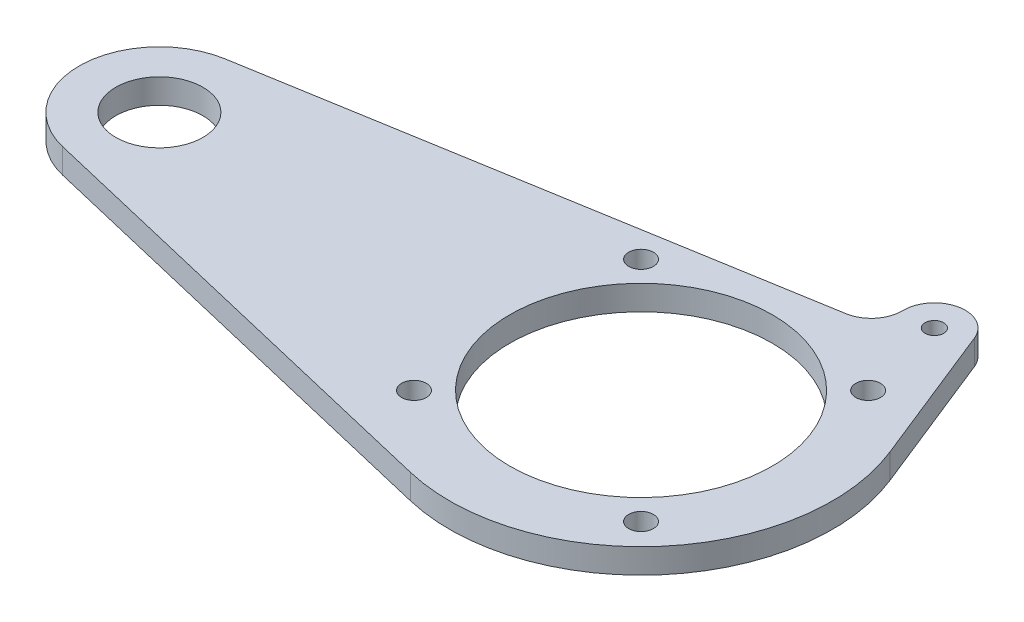
SolidWorks part; units mm, degrees
ref_plane "Front Plane" through (0, 0, 0) normal (0, 0, 1) x (1, 0, 0)
ref_plane "Top Plane" through (0, 0, 0) normal (0, 1, 0) x (1, 0, 0)
ref_plane "Right Plane" through (0, 0, 0) normal (1, 0, 0) x (0, 0, -1)
sketch "Sketch1" plane through (0, 0, 0) normal (0, 1, 0) x (1, 0, 0)
  line L0 (-80.1667, 12.8182) -> (5.8356, 27.3552)
  line L1 (-78, 0) -> (0, 0) construction
  line L2 (-81, -12.6491) -> (-7.1538, -30.1633)
  line L3 (0, 0) -> (15, 32.5) construction
  line L4 (-18.3848, 18.3848) -> (0, 0) construction
  line L5 (19.6422, 34.3575) -> (28.7815, 11.5162)
  circle A4 centre (-78, 0) radius 7.05
  arc A5 (-80.1667, 12.8182) -> (-81, -12.6491) centre (-78, 0) ccw
  arc A6 (-7.1538, -30.1633) -> (28.7815, 11.5162) centre (0, 0) ccw
  circle A7 centre (15, 32.5) radius 1.5
  circle A8 centre (0, 0) radius 26 construction
  circle A9 centre (-18.3848, 18.3848) radius 2
  circle A10 centre (18.3848, 18.3848) radius 2
  circle A11 centre (18.3848, -18.3848) radius 2
  circle A12 centre (-18.3848, -18.3848) radius 2
  arc A13 (19.6422, 34.3575) -> (10.0012, 32.3926) centre (15, 32.5) ccw
  arc A14 (5.8356, 27.3552) -> (10.0012, 32.3926) centre (5.0023, 32.2853) ccw
  circle A15 centre (0, 0) radius 17.5 construction
  circle A20 centre (0, 0) radius 21.25
  circle A21 centre (0, 0) radius 28 construction
  dimension "D1" = 15
  dimension "D2" = 32.5
  dimension "D4" = 52
  dimension "D5" = 3
  dimension "D7" = 5
  dimension "D9" = 4
  dimension "D11" = 35
  dimension "D12" = 5
  dimension "D13" = 42.5
  dimension "D3" = 78
  dimension "D6" = 45
  dimension "D14" = 54
extrude "Boss-Extrude1" add sketch "Sketch1" along normal blind 4
